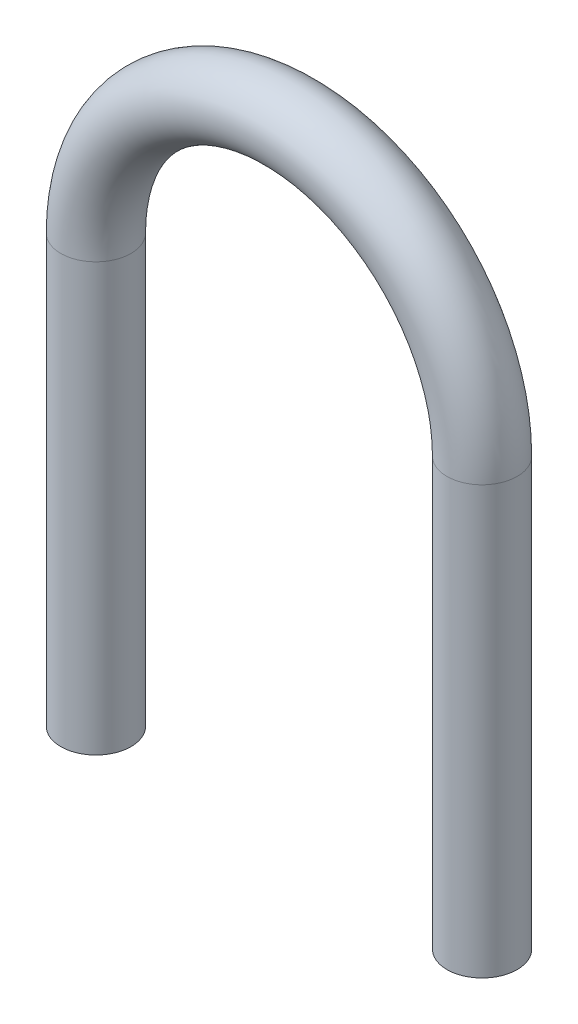
SolidWorks part; units mm, degrees
material "AISI 1020"
ref_plane "Front Plane" through (0, 0, 0) normal (0, 0, 1) x (1, 0, 0)
ref_plane "Top Plane" through (0, 0, 0) normal (0, 1, 0) x (1, 0, 0)
ref_plane "Right Plane" through (0, 0, 0) normal (1, 0, 0) x (0, 0, -1)
sketch "Sketch4" plane through (0, 0, 0) normal (0, 1, 0) x (1, 0, 0)
  circle A0 centre (-16.5, 0) radius 3
  dimension "D1" = 6
  dimension "D2" = 16.5
sketch "Sketch5" plane through (0, 0, 0) normal (0, 0, 1) x (1, 0, 0)
  line L0 (-16.5, 0) -> (-16.5, 36.5)
  line L1 (-13.5, 0) -> (-19.5, 0) construction
  line L2 (16.5, 36.5) -> (16.5, 0)
  arc A0 (16.5, 36.5) -> (-16.5, 36.5) centre (0, 36.5) ccw
  point P5 (0, 53)
  point P9 (-16.5, 0)
  dimension "D2" = 16.5
  dimension "D1" = 53
sweep "Sweep2" add profiles "Sketch4" path "Sketch5"
cosmetic thread "Cosmetic Thread1"
cosmetic thread "Cosmetic Thread2"
